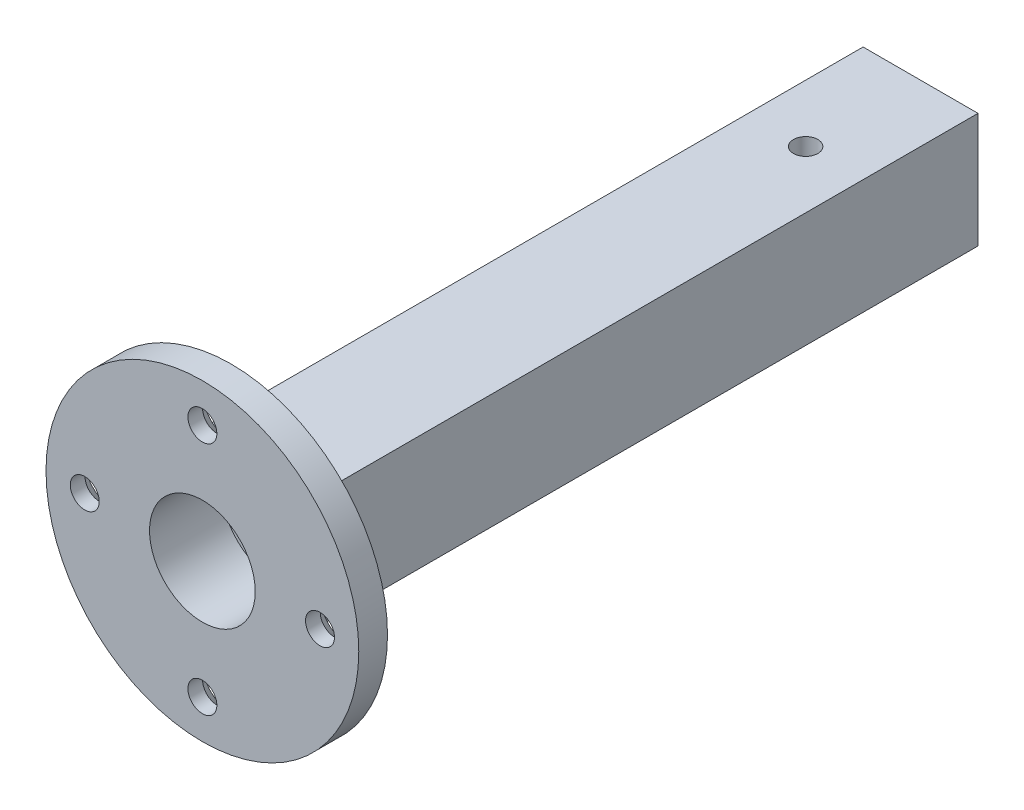
SolidWorks part; units mm, degrees
ref_plane "Front Plane" through (0, 0, 0) normal (0, 0, 1) x (1, 0, 0)
ref_plane "Top Plane" through (0, 0, 0) normal (0, 1, 0) x (1, 0, 0)
ref_plane "Right Plane" through (0, 0, 0) normal (1, 0, 0) x (0, 0, -1)
sketch "Sketch1" plane through (0, 0, 0) normal (0, 0, 1) x (1, 0, 0)
  line L1 (0, 0) -> (12.7, 0)
  line L2 (0, 0) -> (0, 12.7)
  line L3 (0, 12.7) -> (12.7, 12.7)
  line L4 (12.7, 0) -> (12.7, 12.7)
  dimension "D1" = 12.7
  dimension "D2" = 12.7
extrude "Boss-Extrude1" add sketch "Sketch1" along normal blind 76.2
sketch "Sketch4" plane through (0, 0, 0) normal (0, 0, -1) x (-1, 0, 0)
  line L0 (-12.7, 12.7) -> (0, 0) construction
  circle A0 centre (-6.35, 6.35) radius 4.064
  dimension "D1" = 8.128
extrude "Cut-Extrude2" cut sketch "Sketch4" against normal blind 25.4
sketch "Sketch10" plane through (0, 0, 0) normal (0, 0, -1) x (-1, 0, 0)
  circle A0 centre (-6.35, 6.35) radius 5.715
  dimension "D1" = 11.43
extrude "Cut-Extrude3" cut sketch "Sketch10" against normal blind 2.54
sketch "Sketch11" plane through (0, 0, 76.2) normal (0, 0, 1) x (1, 0, 0)
  line L0 (0, 12.7) -> (12.7, 0) construction
  line L1 (0, 0) -> (12.7, 12.7) construction
  circle A0 centre (6.35, 6.35) radius 17.2847
  dimension "D1" = 34.5694
extrude "Boss-Extrude2" add sketch "Sketch11" along normal blind 3.175
sketch "Sketch13" plane through (0, 0, 76.2) normal (0, 0, -1) x (-1, 0, 0)
  line L0 (-6.35, 19.35) -> (-6.35, -6.65) construction
  line L1 (-19.35, 6.35) -> (6.65, 6.35) construction
  circle A0 centre (-6.35, 6.35) radius 13 construction
  circle A1 centre (-6.35, 6.35) radius 17.2847 construction
  dimension "D1" = 26
hole_wizard "CSK for M3 Flat Head Machine Screw1" positions "Sketch15" profile "Sketch14" countersink size "M3" standard "ANSI Metric" end condition through all
sketch "Sketch15" plane through (0, 0, 76.2) normal (0, 0, -1) x (-1, 0, 0)
  point P0 (-6.35, 19.35)
  point P3 (6.65, 6.35)
  point P6 (-6.35, -6.65)
  point P9 (-19.35, 6.35)
sketch "Sketch14" plane through (6.35, 19.35, 76.2) normal (1, 0, 0) x (0, 1, 0)
  line L0 (0, 0) -> (0, 3.175)
  line L1 (0, 3.175) -> (1.6, 3.175)
  line L2 (1.6, 3.175) -> (1.6, 1.55)
  line L3 (1.6, 1.55) -> (3.15, 0)
  line L5 (3.15, 0) -> (0, 0)
  line L6 (-1.6, 1.55) -> (-3.15, 0) construction
  line L11 (0, -6.35) -> (0, 107.95) construction
  dimension "Thru Hole Dia." = 3.2
  dimension "Thru Hole Depth" = 3.175
  dimension "Near C'Sink Dia." = 6.3
  dimension "Near C'Sink Angle" = 90
fillet "Fillet1" radius 1.27 4 edges at (6.35, 0, 76.2) (0, 6.35, 76.2) (6.35, 12.7, 76.2) (12.7, 6.35, 76.2)
sketch "Sketch16" plane through (0, 0, 79.375) normal (0, 0, 1) x (1, 0, 0)
  circle A0 centre (6.35, 6.35) radius 5.842
  circle A1 centre (6.35, 6.35) radius 17.2847 construction
  dimension "D1" = 11.684
extrude "Cut-Extrude4" cut sketch "Sketch16" against normal blind 8
sketch "Sketch17" plane through (0, 12.7, 0) normal (0, 1, 0) x (1, 0, 0)
  line L0 (0, -74.93) -> (0, 0) construction
  line L1 (12.7, 0) -> (0, 0) construction
  circle A0 centre (6.35, -12.7) radius 1.3462
  dimension "D3" = 2.6924
  dimension "D1" = 6.35
  dimension "D2" = 12.7
extrude "Cut-Extrude5" cut sketch "Sketch17" against normal blind 8
